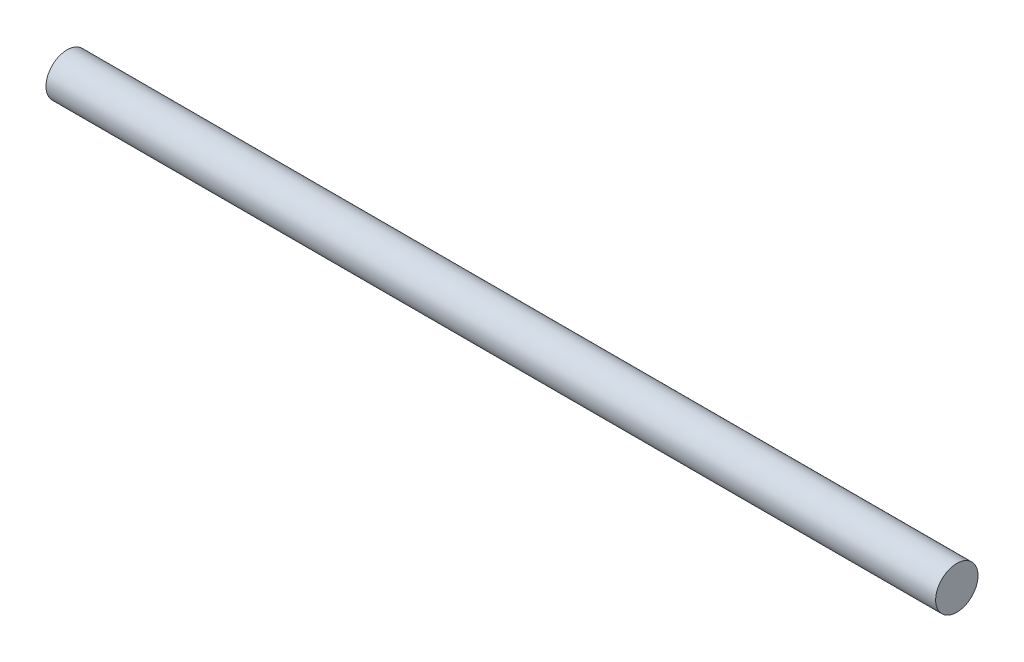
SolidWorks part; units mm, degrees
ref_plane "Front Plane" through (0, 0, 0) normal (0, 0, 1) x (1, 0, 0)
ref_plane "Top Plane" through (0, 0, 0) normal (0, 1, 0) x (1, 0, 0)
ref_plane "Right Plane" through (0, 0, 0) normal (1, 0, 0) x (0, 0, -1)
sketch "Sketch1" plane through (0, 0, 0) normal (1, 0, 0) x (0, 0, -1)
  circle A0 centre (0, 0) radius 4.7625
  dimension "D1" = 9.525
extrude "Boss-Extrude1" add sketch "Sketch1" along normal blind 200
